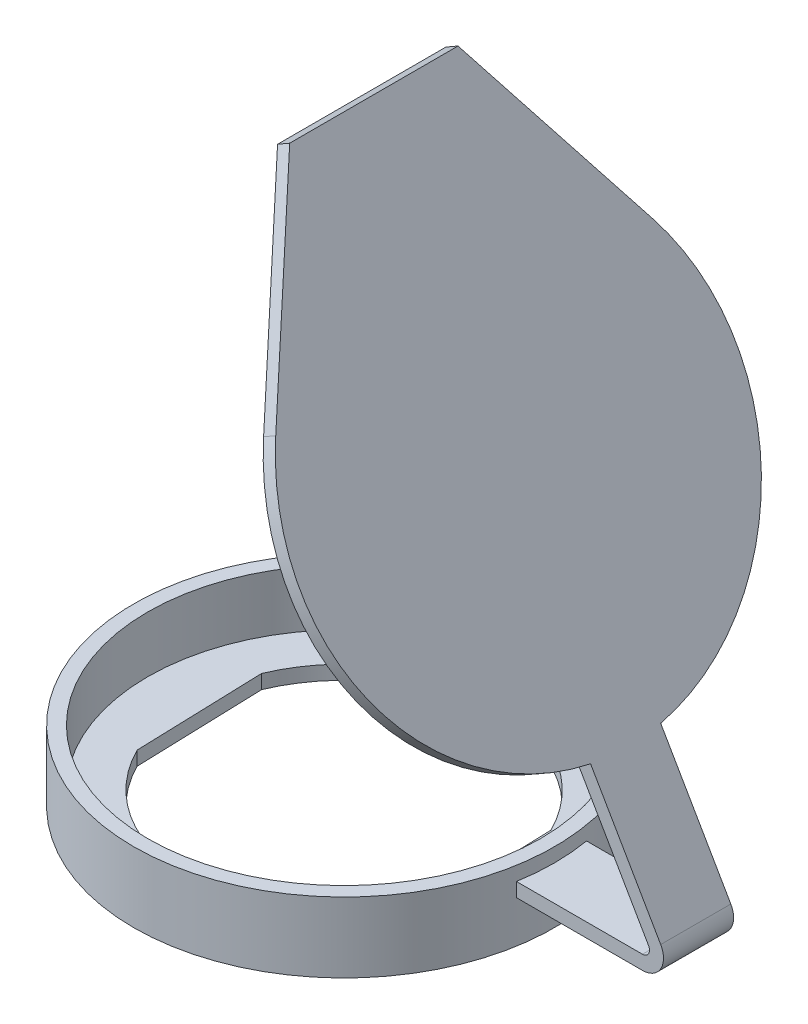
SolidWorks part; units mm, degrees
ref_plane "前视基准面" through (0, 0, 0) normal (0, 0, 1) x (1, 0, 0)
ref_plane "上视基准面" through (0, 0, 0) normal (0, 1, 0) x (1, 0, 0)
ref_plane "右视基准面" through (0, 0, 0) normal (1, 0, 0) x (0, 0, -1)
sketch "草图1" plane through (0, 0, 0) normal (0, 1, 0) x (1, 0, 0)
  circle A0 centre (0, 0) radius 15
  dimension "D1" = 30
extrude "凸台-拉伸1" add sketch "草图1" along normal blind 5
shell "抽壳1" thickness 1
sketch "草图2" plane through (0, 1, 0) normal (0, 1, 0) x (1, 0, 0)
  line L1 (-10.1414, 4.2606) -> (-9.8484, -4.8999)
  line L2 (-4.2606, -10.1414) -> (4.8999, -9.8484)
  line L3 (10.1414, -4.2606) -> (9.8484, 4.8999)
  line L4 (4.2606, 10.1414) -> (-4.8999, 9.8484)
  arc A0 (-9.8484, -4.8999) -> (-4.2606, -10.1414) centre (0, 0) ccw
  circle A1 centre (0, 0) radius 10 construction
  arc A2 (4.8999, -9.8484) -> (10.1414, -4.2606) centre (0, 0) ccw
  arc A3 (-4.8999, 9.8484) -> (-10.1414, 4.2606) centre (0, 0) ccw
  arc A4 (9.8484, 4.8999) -> (4.2606, 10.1414) centre (0, 0) ccw
  point P3 (0, 0)
  point P9 (-6.9453, 6.5149)
  dimension "D1" = 22
  dimension "D2" = 20
extrude "切除-拉伸1" cut sketch "草图2" against normal blind 5
ref_plane "基准面1" through (0, 3, 0) normal (0, -1, 0) x (-1, 0, 0)
sketch "草图3" plane through (0, 3, 0) normal (0, -1, 0) x (-1, 0, 0)
  line L0 (0, 0) -> (-24.8984, 0) construction
  line L1 (-14.7902, 2.5) -> (-23.775, 2.5)
  line L3 (-14.7902, -2.5) -> (-23.775, -2.5)
  line L4 (-23.775, 2.5) -> (-23.775, -2.5)
  arc A0 (-14.7902, 2.5) -> (-14.7902, -2.5) centre (0, 0) ccw
  circle A2 centre (0, 0) radius 15 construction
  point P8 (0, 0)
  point P11 (0, 0)
  point P12 (0, 0)
  point P15 (-5.4408, 1.8695)
  dimension "D2" = 5
extrude "凸台-拉伸2" add sketch "草图3" against normal blind 1
ref_plane "基准面2" through (19.5633, 11.2949, 0) normal (-0.866, -0.5, 0) x (0, 0, 1)
sketch "草图4" plane through (0, 0, 0) normal (0, 0, 1) x (1, 0, 0)
  line L0 (20.074, 13.9103) -> (19.208, 13.4103)
  line L1 (23.775, 3) -> (23.775, 4)
  line L2 (8.7993, 29.9386) -> (30.3273, -7.3489) construction
  line L3 (23.775, 4) -> (14.7902, 4) construction
  line L4 (23.775, 3) -> (14.7902, 3) construction
  line L5 (25.074, 5.25) -> (20.074, 13.9103)
  line L6 (24.208, 4.75) -> (19.208, 13.4103)
  arc A0 (23.775, 4) -> (24.208, 4.75) centre (23.775, 4.5) ccw
  arc A1 (23.775, 3) -> (25.074, 5.25) centre (23.775, 4.5) ccw
  point P2 (0, 0)
  dimension "D2" = 1
  dimension "D1" = 10
  dimension "D3" = 60
extrude "凸台-拉伸3" add sketch "草图4" along normal mid plane 5
sketch "草图5" plane through (21.0788, 12.1699, 0) normal (-0.866, -0.5, 0) x (0, 0, 1)
  line L0 (6, 37.9144) -> (-6, 37.9144)
  line L1 (-6, 37.9144) -> (-13.4234, 25.0567)
  line L3 (13.4234, 25.0567) -> (6, 37.9144)
  line L4 (0, 0) -> (0, 42.5399) construction
  arc A0 (-13.4234, 25.0567) -> (13.4234, 25.0567) centre (0, 17.3067) ccw
  dimension "D1" = 31
  dimension "D2" = 120
  dimension "D3" = 120
  dimension "D4" = 12
extrude "凸台-拉伸6" add sketch "草图5" along normal blind 1
sketch "草图6" plane through (20.2128, 11.6699, 0) normal (-0.866, -0.5, 0) x (0, 0, 1)
  circle A1 centre (0, 17.3067) radius 14
  arc A2 (2.5, 2.0096) -> (13.4234, 25.0567) centre (0, 17.3067) ccw construction
  circle A3 centre (0, 17.3067) radius 12.5
  dimension "D1" = 28
  dimension "D2" = 1.5
extrude "凸台-拉伸7" add sketch "草图6" along normal blind 1.5
